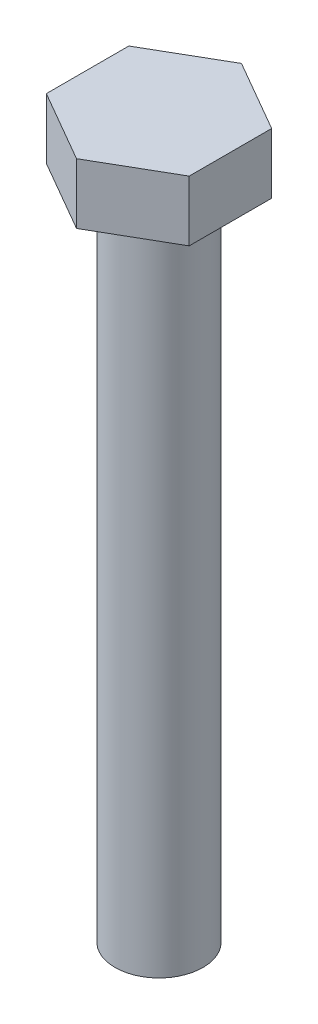
SolidWorks part; units mm, degrees
material "Acier allié"
ref_plane "Plan de face" through (0, 0, 0) normal (0, 0, 1) x (1, 0, 0)
ref_plane "Plan de dessus" through (0, 0, 0) normal (0, 1, 0) x (1, 0, 0)
ref_plane "Plan de droite" through (0, 0, 0) normal (1, 0, 0) x (0, 0, -1)
sketch "Esquisse1" plane through (0, 0, 0) normal (0, 1, 0) x (1, 0, 0)
  line L1 (6.5, 3.7528) -> (0, 7.5056)
  line L2 (0, 7.5056) -> (-6.5, 3.7528)
  line L3 (-6.5, 3.7528) -> (-6.5, -3.7528)
  line L4 (-6.5, -3.7528) -> (0, -7.5056)
  line L5 (0, -7.5056) -> (6.5, -3.7528)
  line L6 (6.5, -3.7528) -> (6.5, 3.7528)
  circle A0 centre (0, 0) radius 6.5 construction
  dimension "D1" = 13
extrude "Boss.-Extru.1" add sketch "Esquisse1" along normal blind 5.5
sketch "Esquisse2" plane through (0, 0, 0) normal (0, 1, 0) x (1, 0, 0)
  circle A0 centre (0, 0) radius 4
  dimension "D1" = 8
extrude "Boss.-Extru.2" add sketch "Esquisse2" against normal blind 60
